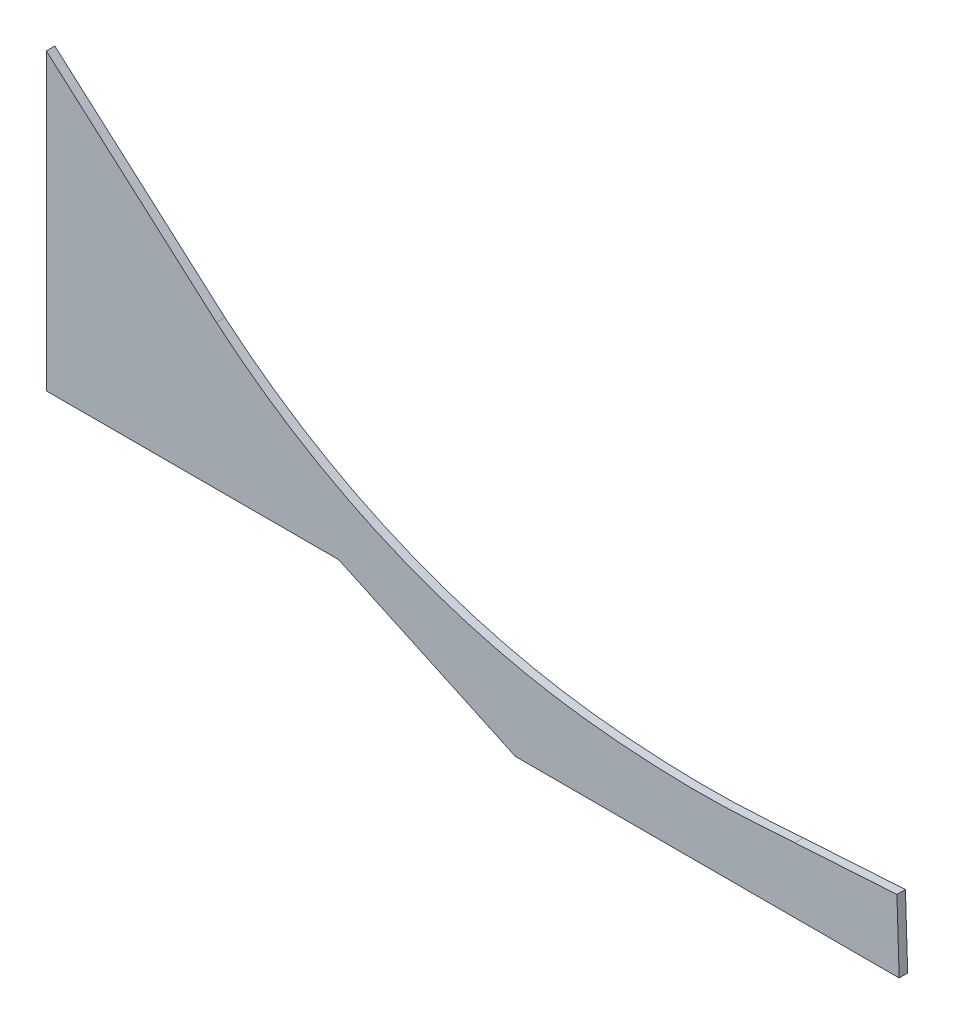
SolidWorks part; units mm, degrees
ref_plane "Přední rovina" through (0, 0, 0) normal (0, 0, 1) x (1, 0, 0)
ref_plane "Horní rovina" through (0, 0, 0) normal (0, 1, 0) x (1, 0, 0)
ref_plane "Pravá rovina" through (0, 0, 0) normal (1, 0, 0) x (0, 0, -1)
sketch "Skica1" plane through (0, 0, 0) normal (0, 0, 1) x (1, 0, 0)
  line L0 (-50, 16.9664) -> (-70, 34.6135)
  line L1 (-70, 0) -> (-70, 57.4213) construction
  line L2 (-70, 34.6135) -> (-70, 0)
  line L3 (-70, 0) -> (-35.6406, 0)
  line L4 (-61.601, 0) -> (22.1755, 0) construction
  line L5 (-35.6406, 0) -> (-14.8557, -9.6442)
  line L6 (-14.8557, -9.6442) -> (30.2643, -9.6442)
  line L7 (30.2643, -9.6442) -> (30, -1.2666)
  line L8 (30, 0) -> (30, 25) construction
  line L9 (18, -2.0111) -> (30, -1.2666)
  spline S0 degree 3 poles (-50, 16.9664) (-43.9912, 11.8716) (-34.1776, 5.7956) (-20.1816, 0.7871) (-10.0924, -1.4578) (-0.0263, -2.4566) (9.3436, -2.6427) (15.3338, -2.1765) (18, -2.0111) knots 0 0 0 0 0.32539 0.471835 0.613059 0.751676 0.889538 1 1 1 1
extrude "Přidat vysunutím1" add sketch "Skica1" along normal blind 1 contours L5 L6 L7 L9 S0 L0 L2 L3
